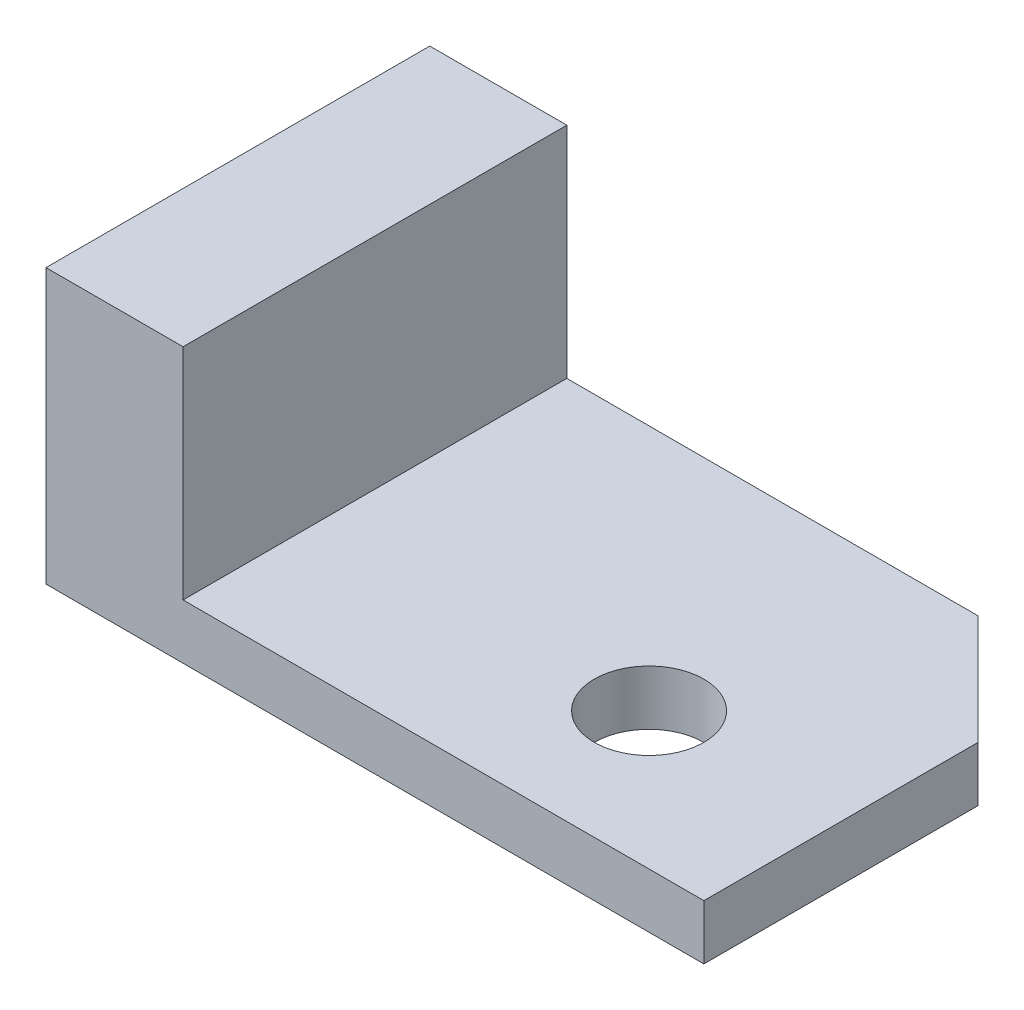
SolidWorks part; units mm, degrees
ref_plane "Front Plane" through (0, 0, 0) normal (0, 0, 1) x (1, 0, 0)
ref_plane "Top Plane" through (0, 0, 0) normal (0, 1, 0) x (1, 0, 0)
ref_plane "Right Plane" through (0, 0, 0) normal (1, 0, 0) x (0, 0, -1)
sketch "Sketch1" plane through (0, 0, 0) normal (0, 1, 0) x (1, 0, 0)
  line L1 (0, 0) -> (120, 0)
  line L2 (0, 0) -> (0, 70)
  line L3 (0, 70) -> (120, 70)
  line L4 (120, 0) -> (120, 70)
  dimension "D1" = 120
  dimension "D2" = 70
extrude "Boss-Extrude1" add sketch "Sketch1" along normal blind 10
sketch "Sketch2" plane through (0, 10, 0) normal (0, 1, 0) x (1, 0, 0)
  line L0 (120, 70) -> (0, 70) construction
  line L1 (0, 0) -> (25, 0)
  line L2 (0, 0) -> (0, 70)
  line L3 (0, 70) -> (25, 70)
  line L4 (25, 0) -> (25, 70)
  dimension "D1" = 25
extrude "Boss-Extrude2" add sketch "Sketch2" along normal blind 40
sketch "Sketch3" plane through (0, 0, 0) normal (0, 1, 0) x (1, 0, 0)
  circle A0 centre (85, 25) radius 10
  dimension "D1" = 20
  dimension "D2" = 85
  dimension "D3" = 25
extrude "Cut-Extrude1" cut sketch "Sketch3" along normal through all
chamfer "Chamfer1" distance 20 1 edges at (120, 5, -70)
